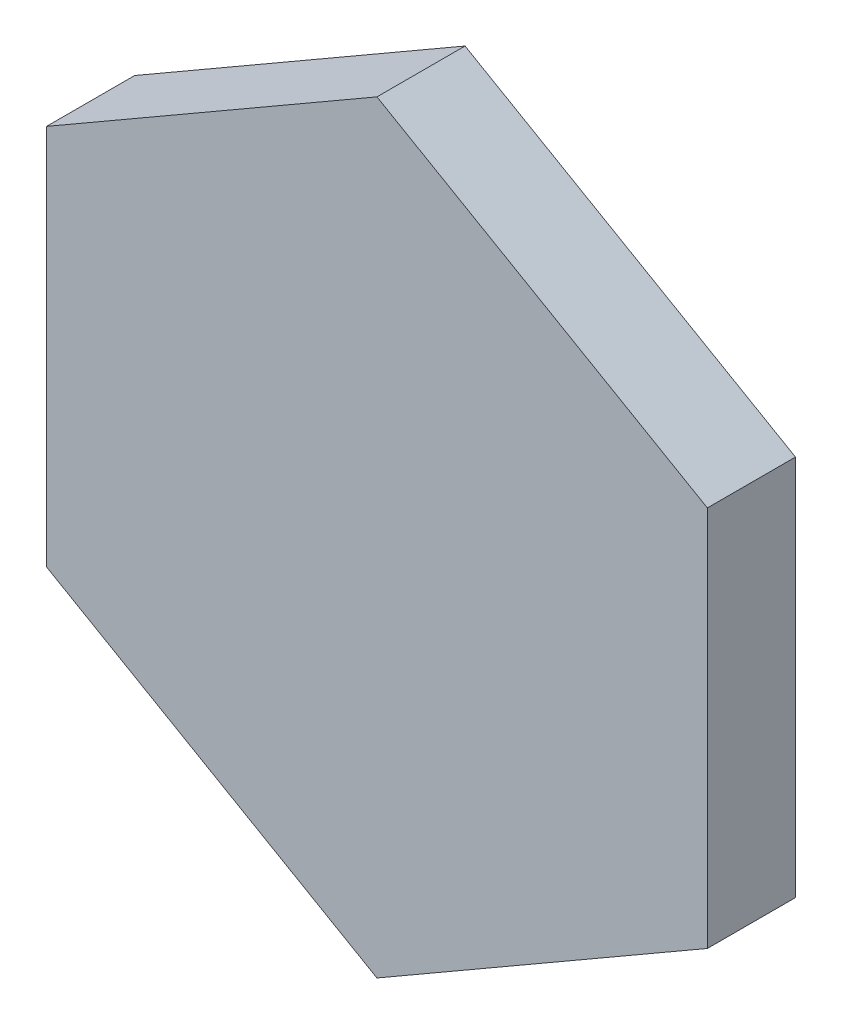
SolidWorks part; units mm, degrees
ref_plane "Front Plane" through (0, 0, 0) normal (0, 0, 1) x (1, 0, 0)
ref_plane "Top Plane" through (0, 0, 0) normal (0, 1, 0) x (1, 0, 0)
ref_plane "Right Plane" through (0, 0, 0) normal (1, 0, 0) x (0, 0, -1)
sketch "Sketch1" plane through (0, 0, 0) normal (0, 0, 1) x (1, 0, 0)
  line L1 (75, 43.3013) -> (0, 86.6025)
  line L2 (0, 86.6025) -> (-75, 43.3013)
  line L3 (-75, 43.3013) -> (-75, -43.3013)
  line L4 (-75, -43.3013) -> (0, -86.6025)
  line L5 (0, -86.6025) -> (75, -43.3013)
  line L6 (75, -43.3013) -> (75, 43.3013)
  circle A0 centre (0, 0) radius 75 construction
  dimension "D1" = 150
extrude "Boss-Extrude1" add sketch "Sketch1" along normal blind 20
